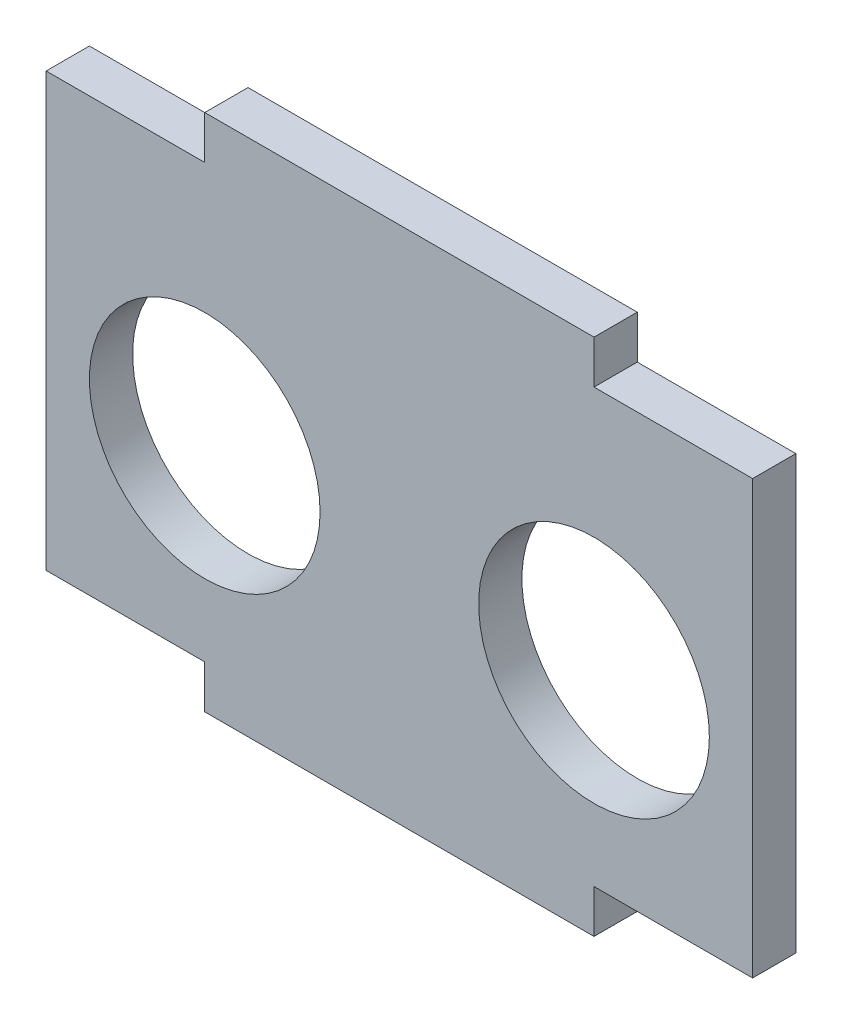
SolidWorks part; units mm, degrees
ref_plane "Front Plane" through (0, 0, 0) normal (0, 0, 1) x (1, 0, 0)
ref_plane "Top Plane" through (0, 0, 0) normal (0, 1, 0) x (1, 0, 0)
ref_plane "Right Plane" through (0, 0, 0) normal (1, 0, 0) x (0, 0, -1)
sketch "Model" plane through (0, 0, 0) normal (0, 0, 1) x (1, 0, 0)
  line L0 (11.9498, 0.8807) -> (11.9498, 30.8807)
  line L1 (60.9498, 0.8972) -> (60.9498, 30.8972)
  line L2 (11.9498, 0.8807) -> (22.9498, 0.8844)
  line L3 (11.9498, 30.8807) -> (22.9498, 30.8844)
  line L4 (22.9498, -2.1156) -> (22.9498, 0.8844)
  line L5 (49.9498, -2.1065) -> (49.9498, 0.8935)
  line L6 (22.9498, -2.1156) -> (49.9498, -2.1065)
  line L7 (22.9498, 33.8844) -> (49.9498, 33.8935)
  line L8 (49.9498, 30.8935) -> (60.9498, 30.8972)
  line L9 (22.9498, 30.8844) -> (22.9498, 33.8844)
  line L10 (49.9498, 30.8935) -> (49.9498, 33.8935)
  line L11 (49.9498, 0.8935) -> (60.9498, 0.8972)
  circle A0 centre (22.9498, 13.8797) radius 8
  circle A1 centre (49.9498, 13.8797) radius 8
extrude "Boss-Extrude1" add sketch "Model" along normal blind 3
